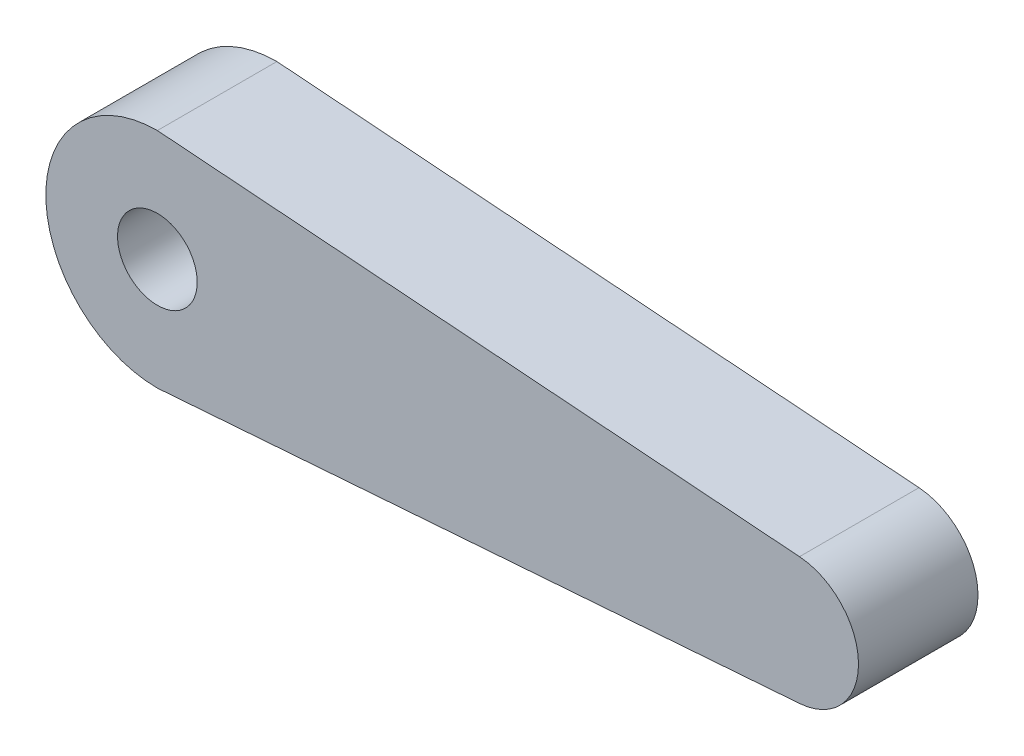
SolidWorks part; units mm, degrees
ref_plane "Plan de face" through (0, 0, 0) normal (0, 0, 1) x (1, 0, 0)
ref_plane "Plan de dessus" through (0, 0, 0) normal (0, 1, 0) x (1, 0, 0)
ref_plane "Plan de droite" through (0, 0, 0) normal (1, 0, 0) x (0, 0, -1)
sketch "Esquisse1" plane through (0, 0, 0) normal (0, 0, 1) x (1, 0, 0)
  line L0 (0, 0) -> (80, 0) construction
  line L1 (-14, 0) -> (0, 0) construction
  line L2 (0, -14) -> (0, 14) construction
  line L3 (50, 0) -> (80.5961, 0) construction
  line L4 (80.5961, -7.9778) -> (80.5961, 7.9778) construction
  line L5 (80.5961, 7.9778) -> (0, 14)
  line L6 (80.5961, -7.9778) -> (0, -14)
  arc A0 (0, 14) -> (0, -14) centre (0, 0) ccw
  arc A1 (80.5961, 7.9778) -> (80.5961, -7.9778) centre (80, 0) cw
  dimension "D2" = 14
  dimension "D3" = 8
  dimension "D1" = 80
extrude "Boss.-Extru.1" add sketch "Esquisse1" along normal blind 15
sketch "Esquisse3" plane through (0, 0, 15) normal (0, 0, 1) x (1, 0, 0)
  circle A0 centre (0, 0) radius 5
  dimension "D1" = 10
extrude "Enlèv. mat.-Extru.1" cut sketch "Esquisse3" against normal through all both and the other way through all
